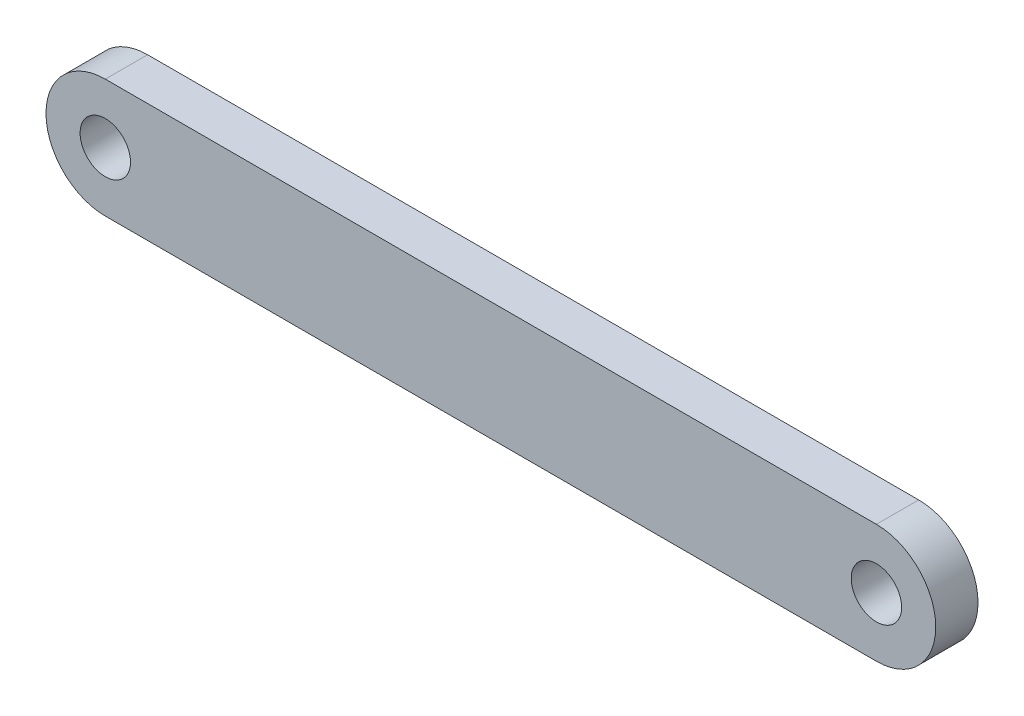
SolidWorks part; units mm, degrees
material "Pine"
ref_plane "Front" through (0, 0, 0) normal (0, 0, 1) x (1, 0, 0)
ref_plane "Top" through (0, 0, 0) normal (0, 1, 0) x (1, 0, 0)
ref_plane "Right" through (0, 0, 0) normal (1, 0, 0) x (0, 0, -1)
sketch "Sketch1" plane through (0, 0, 0) normal (0, 0, 1) x (1, 0, 0)
  line L1 (-30, 4) -> (30, 4)
  line L2 (-30, 4) -> (-30, -4)
  line L3 (-30, -4) -> (30, -4)
  line L4 (30, 4) -> (30, -4)
  line L5 (-30, 4) -> (30, -4) construction
  line L6 (-30, -4) -> (30, 4) construction
  point P0 (0, 0)
  dimension "D1" = 60
  dimension "D2" = 8
extrude "Boss-Extrude1" add sketch "Sketch1" along normal blind 2.85
sketch "Sketch2" plane through (0, 0, 2.85) normal (0, 0, 1) x (1, 0, 0)
  line L0 (26, -4) -> (31, -4)
  line L1 (31, -4) -> (31, 4)
  line L2 (31, 4) -> (26, 4)
  line L3 (30, -4) -> (30, 4) construction
  line L4 (30, 4) -> (-30, 4) construction
  line L5 (-30, -4) -> (30, -4) construction
  arc A0 (26, -4) -> (26, 4) centre (26, 0) ccw
  dimension "D1" = 1
extrude "Cut-Extrude1" cut sketch "Sketch2" against normal through all
sketch "Sketch3" plane through (0, 0, 2.85) normal (0, 0, 1) x (1, 0, 0)
  circle A0 centre (26, 0) radius 1.7
  dimension "D1" = 3.4
extrude "Cut-Extrude2" cut sketch "Sketch3" against normal through all
mirror "Mirror1" about plane through (0, 0, 0) normal (1, 0, 0) of "Cut-Extrude2", "Cut-Extrude1"
